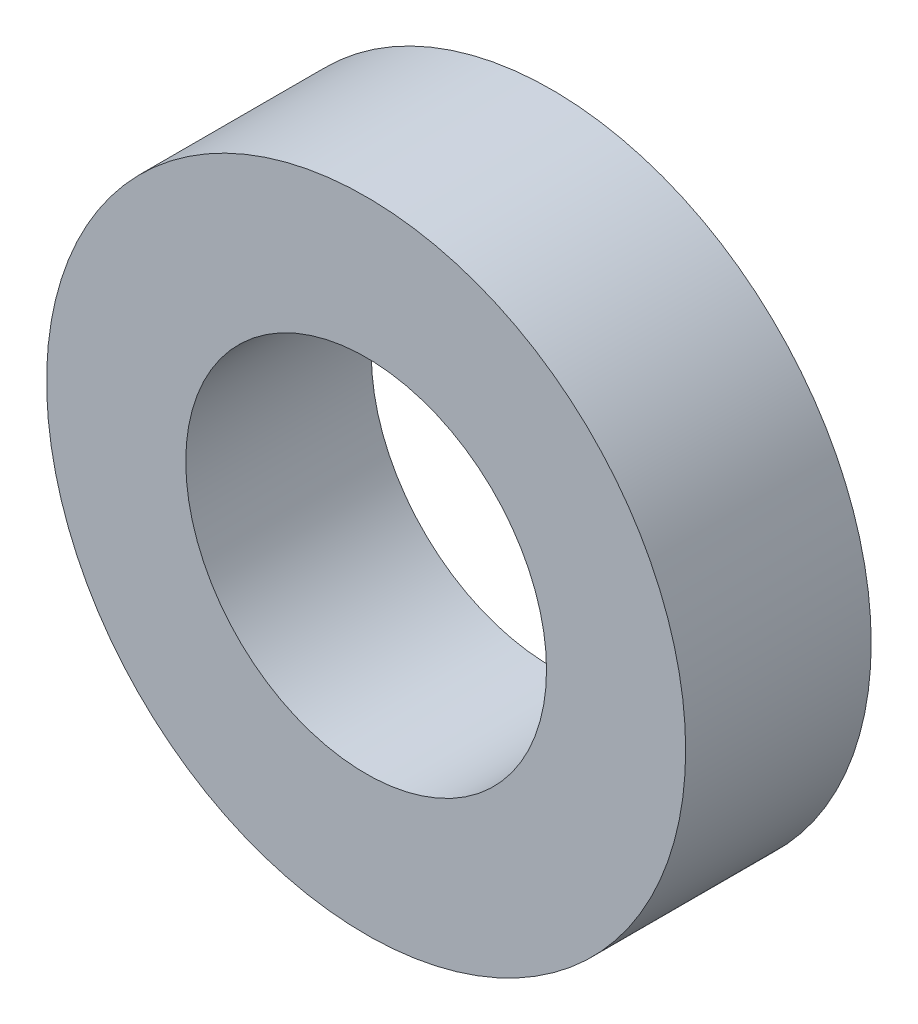
SolidWorks part; units mm, degrees
ref_plane "前视基准面" through (0, 0, 0) normal (0, 0, 1) x (1, 0, 0)
ref_plane "上视基准面" through (0, 0, 0) normal (0, 1, 0) x (1, 0, 0)
ref_plane "右视基准面" through (0, 0, 0) normal (1, 0, 0) x (0, 0, -1)
sketch "草图1" plane through (0, 0, 0) normal (0, 0, 1) x (1, 0, 0)
  circle A0 centre (0, 0) radius 31
  circle A1 centre (0, 0) radius 17.5
  dimension "D1" = 35
  dimension "D2" = 62
extrude "凸台-拉伸1" add sketch "草图1" along normal blind 18
